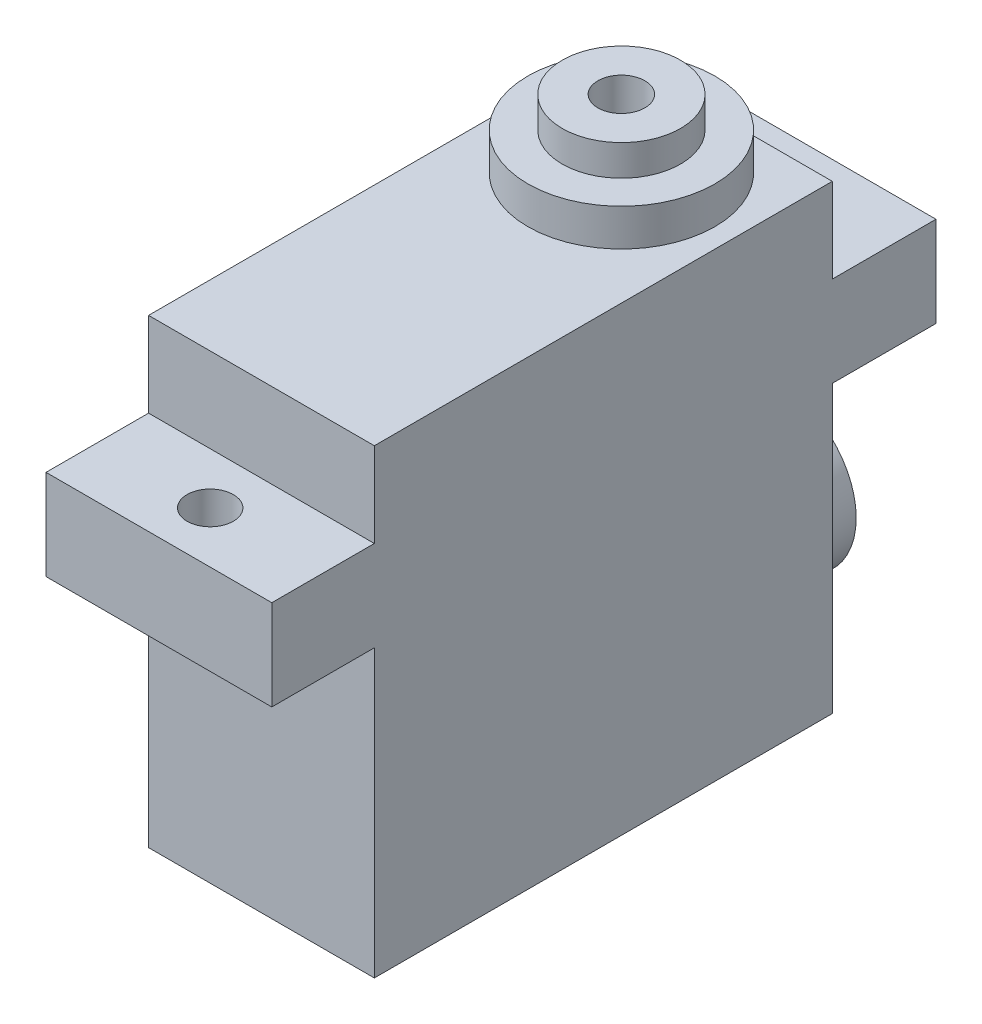
SolidWorks part; units mm, degrees
ref_plane "Front Plane" through (0, 0, 0) normal (0, 0, 1) x (1, 0, 0)
ref_plane "Top Plane" through (0, 0, 0) normal (0, 1, 0) x (1, 0, 0)
ref_plane "Right Plane" through (0, 0, 0) normal (1, 0, 0) x (0, 0, -1)
sketch "Sketch1" plane through (0, 0, 0) normal (0, 1, 0) x (1, 0, 0)
  line L1 (0, 0) -> (15.24, 0)
  line L2 (0, 0) -> (0, 30.9118)
  line L3 (0, 30.9118) -> (15.24, 30.9118)
  line L4 (15.24, 0) -> (15.24, 30.9118)
  dimension "D1" = 15.24
  dimension "D2" = 30.9118
extrude "Boss-Extrude1" add sketch "Sketch1" along normal blind 31.115
sketch "Sketch2" plane through (0, 0, 0) normal (0, 0, 1) x (1, 0, 0)
  line L0 (0, 31.115) -> (0, 0) construction
  line L1 (0, 25.4) -> (15.24, 25.4)
  line L2 (0, 25.4) -> (0, 19.304)
  line L3 (0, 19.304) -> (15.24, 19.304)
  line L4 (15.24, 25.4) -> (15.24, 19.304)
  line L5 (15.24, 31.115) -> (15.24, 0) construction
  line L6 (0, 0) -> (15.24, 0) construction
  dimension "D1" = 19.304
  dimension "D2" = 6.096
extrude "Boss-Extrude2" add sketch "Sketch2" along normal blind 6.9215 and the other way blind 37.9095
sketch "Sketch3" plane through (0, 0, -30.9118) normal (0, 0, -1) x (-1, 0, 0)
  line L0 (-15.24, 0) -> (0, 0) construction
  circle A0 centre (-7.62, 8.2804) radius 5.2705
  dimension "D1" = 10.541
  dimension "D2" = 8.2804
extrude "Boss-Extrude3" add sketch "Sketch3" along normal blind 3.9624
sketch "Sketch4" plane through (0, 31.115, 0) normal (0, 1, 0) x (1, 0, 0)
  line L0 (15.24, 30.9118) -> (0, 30.9118) construction
  circle A0 centre (7.62, 24.2951) radius 6.3119
  dimension "D1" = 12.6238
  dimension "D2" = 6.6167
extrude "Boss-Extrude4" add sketch "Sketch4" along normal blind 2.5019
sketch "Sketch8" plane through (0, 25.4, 0) normal (0, 1, 0) x (1, 0, 0)
  circle A0 centre (7.62, -3.4608) radius 1.5621
  dimension "D1" = 3.1242
extrude "Cut-Extrude1" cut sketch "Sketch8" against normal up to next
sketch "Sketch9" plane through (0, 25.4, 0) normal (0, 1, 0) x (1, 0, 0)
  circle A0 centre (7.62, 34.4107) radius 1.5621
  dimension "D1" = 3.1242
extrude "Cut-Extrude2" cut sketch "Sketch9" against normal up to next
sketch "Sketch10" plane through (0, 33.6169, 0) normal (0, 1, 0) x (1, 0, 0)
  circle A0 centre (7.62, 24.2951) radius 3.9942
  circle A8 centre (7.62, 24.2951) radius 6.3119 construction
  dimension "D1" = 7.9883
extrude "Boss-Extrude5" add sketch "Sketch10" along normal blind 2.0828
sketch "Sketch11" plane through (0, 35.6997, 0) normal (0, 1, 0) x (1, 0, 0)
  line L0 (3.6258, 24.2951) -> (11.6141, 24.2951) construction
  line L1 (7.62, 26.2001) -> (7.62, 22.3901)
  line L2 (7.62, 26.2001) -> (7.62, 22.3901)
  line L3 (7.62, 26.2001) -> (22.0599, 26.2001)
  line L4 (7.62, 22.3901) -> (22.0599, 22.3901)
  line L5 (22.0599, 26.2001) -> (22.0599, 22.3901)
  line L6 (7.62, 26.2001) -> (7.62, 22.3901)
  line L7 (7.62, 26.2001) -> (-6.8199, 26.2001)
  line L8 (7.62, 22.3901) -> (-6.8199, 22.3901)
  line L9 (-6.8199, 26.2001) -> (-6.8199, 22.3901)
  circle A0 centre (7.62, 24.2951) radius 3.9941 construction
  circle A1 centre (7.62, 24.2951) radius 3.9941 construction
  circle M4 centre (7.62, 24.2951) radius 3.9942
  dimension "D1" = 1.905
  dimension "D2" = 1.905
  dimension "D3" = 14.4399
  dimension "D4" = 14.4399
extrude "Boss-Extrude6" [suppressed] add sketch "Sketch11" along normal blind 1.5875 contours L7 L9 L8 M4 | L0 L1 L7 M4 | L0 L8 L6 M4 | L1 L0 L3 M4 | L0 L6 L4 M4 | L5 L3 L4 M4
sketch "Sketch12" plane through (0, 35.6997, 0) normal (0, 1, 0) x (1, 0, 0)
  circle A0 centre (7.6196, 24.3125) radius 3.9768
extrude "Boss-Extrude7" [suppressed] add sketch "Sketch12" along normal blind 2.794
sketch "Sketch13" plane through (0, 35.6997, 0) normal (0, 1, 0) x (1, 0, 0)
  circle A0 centre (7.62, 24.2951) radius 1.5875
  dimension "D1" = 3.175
extrude "Cut-Extrude3" cut sketch "Sketch13" against normal blind 2.54
